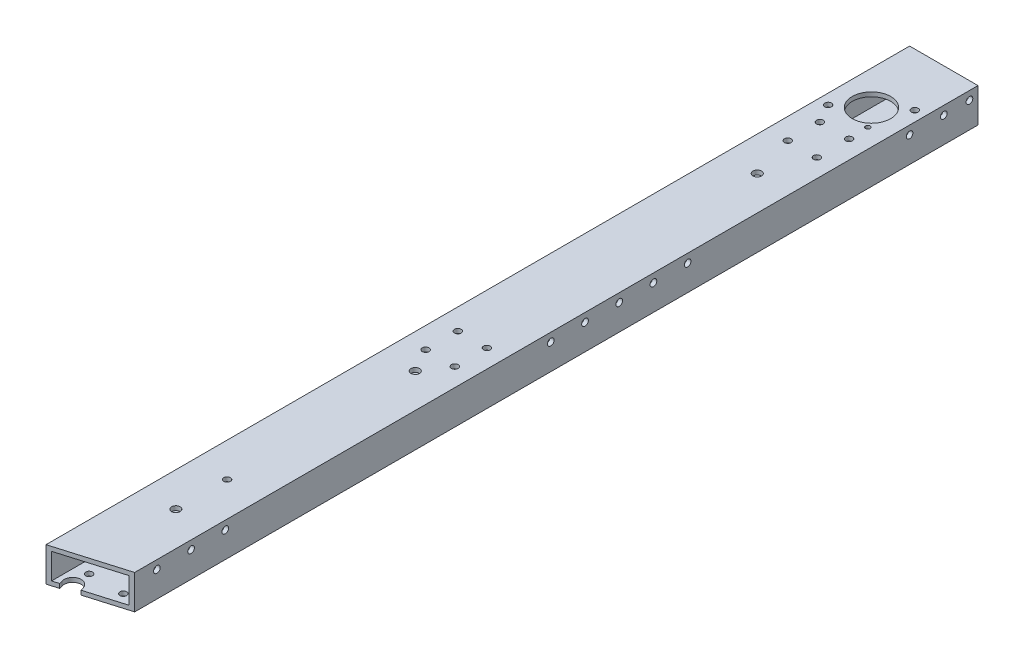
SolidWorks part; units mm, degrees
material "6061 Alloy"
ref_plane "Front Plane" through (0, 0, 0) normal (0, 0, 1) x (1, 0, 0)
ref_plane "Top Plane" through (0, 0, 0) normal (0, 1, 0) x (1, 0, 0)
ref_plane "Right Plane" through (0, 0, 0) normal (1, 0, 0) x (0, 0, -1)
sketch "Sketch1" plane through (0, 0, 0) normal (0, 0, 1) x (1, 0, 0)
  line L0 (-22.225, 9.525) -> (22.225, 9.525)
  line L2 (-25.4, 12.7) -> (25.4, 12.7)
  line L3 (-25.4, 12.7) -> (-25.4, -12.7)
  line L4 (-25.4, -12.7) -> (25.4, -12.7)
  line L5 (25.4, 12.7) -> (25.4, -12.7)
  line L10 (22.225, 9.525) -> (22.225, -9.525)
  line L11 (-22.225, -9.525) -> (22.225, -9.525)
  line L12 (-22.225, 9.525) -> (-22.225, -9.525)
  point P12 (0, 12.7)
  point P14 (25.4, 0)
  dimension "Wall Thickness" = 3.175
  dimension "Outside Width" = 50.8
  dimension "Outside Height" = 25.4
  dimension "Inside Height" = 19.05
  dimension "Inside Width" = 44.45
sketch "Sketch2" plane through (0, 0, 0) normal (1, 0, 0) x (0, 0, -1)
  line L0 (320.675, 0) -> (-320.675, 0)
  point P4 (0, 0)
  point P7 (-320.675, 0)
  point P10 (320.675, 0)
  dimension "Length" = 641.35
sketch "Sketch3" plane through (0, 0, 0) normal (0, 0, 1) x (1, 0, 0)
  line L21 (25.4, 12.7) -> (-25.4, 12.7)
  line L22 (25.4, -12.7) -> (25.4, 12.7)
  line L23 (-25.4, -12.7) -> (25.4, -12.7)
  line L24 (-25.4, 12.7) -> (-25.4, -12.7)
  line L25 (25.4, 12.7) -> (-25.4, 12.7)
  line L26 (25.4, -12.7) -> (25.4, 12.7)
  line L27 (-25.4, -12.7) -> (25.4, -12.7)
  line L28 (-25.4, 12.7) -> (-25.4, -12.7)
  line L29 (22.225, 9.525) -> (-22.225, 9.525)
  line L30 (22.225, -9.525) -> (22.225, 9.525)
  line L31 (-22.225, -9.525) -> (22.225, -9.525)
  line L32 (-22.225, 9.525) -> (-22.225, -9.525)
  line L33 (22.225, 9.525) -> (-22.225, 9.525)
  line L34 (22.225, -9.525) -> (22.225, 9.525)
  line L35 (-22.225, -9.525) -> (22.225, -9.525)
  line L36 (-22.225, 9.525) -> (-22.225, -9.525)
  dimension "D1" = 0
  dimension "D2" = 0
extrude "Boss-Extrude1" add sketch "Sketch3" along normal up to vertex (320.675 mm away) and the other way up to vertex (320.675 mm away) up to point (0, 0, 320.675) other way up to point (0, 0, -320.675)
sketch "Drawing Reference" plane through (0, 0, 0) normal (1, 0, 0) x (0, 0, -1)
  line L0 (-320.675, 0) -> (320.675, 0) construction
  line L1 (0, -12.7) -> (0, 12.7) construction
  line L2 (-320.675, -12.7) -> (320.675, -12.7) construction
  line L5 (-320.675, 12.7) -> (320.675, 12.7) construction
  point P7 (-284.099, 0)
  point P8 (284.099, 0)
  dimension "D1" = 36.576
sketch "Sketch4" plane through (0, 12.7, 0) normal (0, 1, 0) x (1, 0, 0)
  line L0 (-25.4, -320.675) -> (25.4, -305.6274)
  line L1 (25.4, -320.675) -> (25.4, 320.675) construction
  line L2 (25.4, -320.675) -> (-25.4, -320.675)
  dimension "D1" = 16.5
extrude "Cut-Extrude1" cut sketch "Sketch4" against normal through all and the other way through all flip side to cut
sketch "Sketch8" plane through (0, 12.7, 0) normal (0, 1, 0) x (1, 0, 0)
  line L0 (0, 320.675) -> (0, 266.954) construction
  line L1 (25.4, 320.675) -> (-25.4, 320.675) construction
  circle A0 centre (0, 266.954) radius 14.2875
  dimension "D1" = 53.721
extrude "Cut-Extrude2" cut sketch "Sketch8" against normal through all
sketch "Sketch9" plane through (0, -12.7, 0) normal (0, -1, 0) x (1, 0, 0)
  line L0 (-12.7762, 284.753) -> (-12.7762, 301.263) construction
  line L1 (-12.7762, 301.263) -> (12.6238, 301.263) construction
  line L2 (12.6238, 301.263) -> (12.6238, 284.753) construction
  line L3 (12.6238, 284.753) -> (-12.7762, 284.753) construction
hole_wizard "#10 Clearance Hole1" positions "Sketch10" profile "Sketch11" hole size "#10" standard "ANSI Inch"
sketch "Sketch10" plane through (0, -12.7, 0) normal (0, -1, 0) x (-1, 0, 0)
  point P0 (-12.6238, -284.753)
  point P3 (12.7762, -284.753)
  point P6 (12.7762, -301.263)
  point P9 (-12.6238, -301.263)
sketch "Sketch11" plane through (12.6238, -12.7, 284.753) normal (1, 0, 0) x (0, 0, -1)
  line L0 (0, 0) -> (0, 6.5757)
  line L1 (0, 6.5757) -> (2.4892, 5.08)
  line L2 (2.4892, 5.08) -> (2.4892, 0)
  line L5 (2.4892, 0) -> (0, 0)
  line L10 (0, 6.5757) -> (-2.4892, 5.08) construction
  line L11 (0, -6.35) -> (0, 107.95) construction
  dimension "Hole Dia." = 4.9784
  dimension "Hole Depth" = 5.08
  dimension "Drill Angle" = 118
sketch "Sketch12" plane through (25.4, 0, 0) normal (1, 0, 0) x (0, 0, -1)
  line L0 (320.675, 533.4) -> (-305.6274, 533.4) construction
  line L1 (320.675, 520.7) -> (320.675, 546.1) construction
  line L2 (-305.6274, 546.1) -> (-305.6274, 520.7) construction
hole_wizard "#10 Clearance Hole2" positions "Sketch13" profile "Sketch14" hole size "#10" standard "ANSI Inch" end condition through all
sketch "Sketch13" plane through (25.4, 0, 0) normal (1, 0, 0) x (0, 0, -1)
  point P0 (314.325, 6.35)
  point P3 (295.275, 6.35)
sketch "Sketch14" plane through (25.4, 6.35, -314.325) normal (0, 1, 0) x (0, 0, -1)
  line L0 (0, 0) -> (0, 50.8)
  line L1 (0, 50.8) -> (2.4892, 50.8)
  line L2 (2.4892, 50.8) -> (2.4892, 0)
  line L5 (2.4892, 0) -> (0, 0)
  line L11 (0, -6.35) -> (0, 107.95) construction
  dimension "Thru Hole Dia." = 4.9784
  dimension "Thru Hole Depth" = 50.8
hole_wizard "#10 Clearance Hole3" positions "Sketch15" profile "Sketch16" hole size "#10" standard "ANSI Inch" end condition through all
sketch "Sketch15" plane through (25.4, 0, 0) normal (1, 0, 0) x (0, 0, -1)
  point P0 (105.029, 6.35)
  point P3 (79.629, 6.35)
  point P6 (54.229, 6.35)
  point P9 (28.829, 6.35)
  point P12 (3.429, 6.35)
  point P24 (-289.1267, 6.3882)
  point P27 (-263.7267, 6.3882)
  point P30 (-238.3267, 6.3882)
sketch "Sketch16" plane through (25.4, 6.35, -105.029) normal (0, 1, 0) x (0, 0, -1)
  line L0 (0, 0) -> (0, 50.8)
  line L1 (0, 50.8) -> (2.4892, 50.8)
  line L2 (2.4892, 50.8) -> (2.4892, 0)
  line L5 (2.4892, 0) -> (0, 0)
  line L11 (0, -6.35) -> (0, 107.95) construction
  dimension "Thru Hole Dia." = 4.9784
  dimension "Thru Hole Depth" = 50.8
sketch "Sketch18" plane through (0, 12.7, 0) normal (0, 1, 0) x (1, 0, 0)
  line L0 (-17.786, 252.537) -> (17.786, 281.371) construction
  line L1 (0, 266.954) -> (11.3559, 252.9444) construction
hole_wizard "#10 Clearance Hole4" positions "Sketch19" profile "Sketch20" hole size "#10" standard "ANSI Inch"
sketch "Sketch19" plane through (0, 12.7, 0) normal (0, 1, 0) x (1, 0, 0)
  point P0 (17.786, 281.371)
  point P3 (-17.786, 252.537)
sketch "Sketch20" plane through (17.786, 12.7, -281.371) normal (1, 0, 0) x (0, 0, 1)
  line L0 (0, 0) -> (0, 6.5757)
  line L1 (0, 6.5757) -> (2.4892, 5.08)
  line L2 (2.4892, 5.08) -> (2.4892, 0)
  line L5 (2.4892, 0) -> (0, 0)
  line L10 (0, 6.5757) -> (-2.4892, 5.08) construction
  line L11 (0, -6.35) -> (0, 107.95) construction
  dimension "Hole Dia." = 4.9784
  dimension "Hole Depth" = 5.08
  dimension "Drill Angle" = 118
sketch "Sketch21" plane through (0, 12.7, 0) normal (0, 1, 0) x (1, 0, 0)
  line L2 (-0.0762, -211.5512) -> (0, -313.1512) construction
  line L3 (-25.4, -320.675) -> (25.4, -305.6274) construction
  dimension "D1" = 101.6
hole_wizard "#10 Clearance Hole5" positions "Sketch22" profile "Sketch23" hole size "#10" standard "ANSI Inch" end condition through all
sketch "Sketch22" plane through (0, 12.7, 0) normal (0, 1, 0) x (1, 0, 0)
  point P0 (-0.0762, -211.5512)
sketch "Sketch23" plane through (-0.0762, 12.7, 211.5512) normal (1, 0, 0) x (0, 0, 1)
  line L0 (0, 0) -> (0, 25.4)
  line L1 (0, 25.4) -> (2.4892, 25.4)
  line L2 (2.4892, 25.4) -> (2.4892, 0)
  line L5 (2.4892, 0) -> (0, 0)
  line L11 (0, -6.35) -> (0, 107.95) construction
  dimension "Thru Hole Dia." = 4.9784
  dimension "Thru Hole Depth" = 25.4
hole_wizard "Tap Drill for #8-32 Tap1" positions "Sketch24" profile "Sketch25" hole size "#8-32" standard "ANSI Inch" end condition through all
sketch "Sketch24" plane through (0, 12.7, 0) normal (0, 1, 0) x (1, 0, 0)
  point P0 (11.3559, 252.9444)
sketch "Sketch25" plane through (11.3559, 12.7, -252.9444) normal (1, 0, 0) x (0, 0, 1)
  line L0 (0, 0) -> (0, 25.4)
  line L1 (0, 25.4) -> (1.7272, 25.4)
  line L2 (1.7272, 25.4) -> (1.7272, 0)
  line L5 (1.7272, 0) -> (0, 0)
  line L11 (0, -6.35) -> (0, 107.95) construction
  dimension "Thru Hole Dia." = 3.4544
  dimension "Thru Hole Depth" = 25.4
hole_wizard "#10 Clearance Hole6" positions "Sketch26" profile "Sketch27" hole size "#10" standard "ANSI Inch" end condition through all
sketch "Sketch26" plane through (0, 12.7, 0) normal (0, 1, 0) x (1, 0, 0)
  point P0 (-9.7957, 238.4743)
  point P3 (11.8451, 238.4743)
  point P6 (11.8451, 214.5983)
  point P9 (-9.7957, 214.5983)
  point P12 (11.8451, -30.4483)
  point P15 (-9.7957, -30.4483)
  point P18 (-9.7957, -54.3243)
  point P21 (11.8451, -54.3243)
sketch "Sketch27" plane through (-9.7957, 12.7, -238.4743) normal (1, 0, 0) x (0, 0, 1)
  line L0 (0, 0) -> (0, 25.4)
  line L1 (0, 25.4) -> (5.2197, 25.4)
  line L2 (2.4892, 22.2589) -> (2.4892, 0)
  line L5 (2.4892, 0) -> (0, 0)
  line L7 (5.2197, 25.4) -> (2.4892, 22.2589)
  line L8 (-5.2197, 25.4) -> (-2.4892, 22.2589) construction
  line L11 (0, -6.35) -> (0, 107.95) construction
  dimension "Thru Hole Dia." = 4.9784
  dimension "Thru Hole Depth" = 25.4
  dimension "Far C'Sink Dia." = 10.4394
  dimension "Far C'Sink Angle" = 82
hole_wizard "#10 (0.1935) Diameter Hole1" positions "Sketch28" profile "Sketch29" hole size "#10" standard "ANSI Inch"
sketch "Sketch28" plane through (25.4, 0, 0) normal (1, 0, 0) x (0, 0, -1)
  point P5 (269.875, 6.35)
sketch "Sketch29" plane through (25.4, 6.35, -269.875) normal (0, 1, 0) x (0, 0, -1)
  line L0 (0, 0) -> (0, 4.7786)
  line L1 (0, 4.7786) -> (2.4574, 3.302)
  line L2 (2.4574, 3.302) -> (2.4574, 0)
  line L5 (2.4574, 0) -> (0, 0)
  line L10 (0, 4.7786) -> (-2.4574, 3.302) construction
  line L11 (0, -6.35) -> (0, 107.95) construction
  dimension "Hole Dia." = 4.9149
  dimension "Hole Depth" = 3.302
  dimension "Drill Angle" = 118
sketch "Sketch30" plane through (0, -12.7, 0) normal (0, 1, 0) x (1, 0, 0)
  line L0 (-25.4, -320.675) -> (-11.4451, -316.5414) construction
  line L1 (-25.4, -320.675) -> (25.4, -305.6274) construction
  line L2 (-11.4451, -316.5414) -> (-12.1665, -314.106) construction
  line L3 (-5.3566, -314.7379) -> (-6.078, -312.3025)
  line L4 (-17.5337, -318.3449) -> (-18.2551, -315.9095)
  line L5 (-5.3566, -314.7379) -> (-17.5337, -318.3449)
  arc A0 (-6.078, -312.3025) -> (-18.2551, -315.9095) centre (-12.1665, -314.106) ccw
  line M41 (25.4, -305.6274) -> (-25.4, -320.675)
  dimension "D1" = 6.35
  dimension "D3" = 2.54
  dimension "D2" = 6.35
extrude "Cut-Extrude4" cut sketch "Sketch30" along normal blind 5.08 contours A0 L3 L4 M41
sketch "Sketch31" plane through (0, 12.7, 0) normal (0, 1, 0) x (1, 0, 0)
  line L0 (0, -313.1512) -> (0, -249.6512) construction
  line L1 (-25.4, -320.675) -> (25.4, -305.6274) construction
  line L2 (0, -249.6512) -> (0, -71.8512) construction
  line L3 (0, -71.8512) -> (0, 182.1488) construction
  dimension "D1" = 63.5
  dimension "D2" = 177.8
  dimension "D3" = 254
hole_wizard "1/4 (0.25) Diameter Hole1" positions "Sketch32" profile "Sketch33" hole size "1/4" standard "ANSI Inch" end condition through all
sketch "Sketch32" plane through (0, 12.7, 0) normal (0, 1, 0) x (1, 0, 0)
  point P9 (0, -71.8512)
  point P12 (0, -249.6512)
  point P15 (0, 182.1488)
sketch "Sketch33" plane through (0, 12.7, 71.8512) normal (1, 0, 0) x (0, 0, 1)
  line L0 (0, 0) -> (0, 25.4)
  line L1 (0, 25.4) -> (3.175, 25.4)
  line L2 (3.175, 25.4) -> (3.175, 0)
  line L5 (3.175, 0) -> (0, 0)
  line L11 (0, -6.35) -> (0, 107.95) construction
  dimension "Thru Hole Dia." = 6.35
  dimension "Thru Hole Depth" = 25.4
equation "\"D1@Drawing Reference\"=\"Outside Width@Sketch1\" * 0.72"
